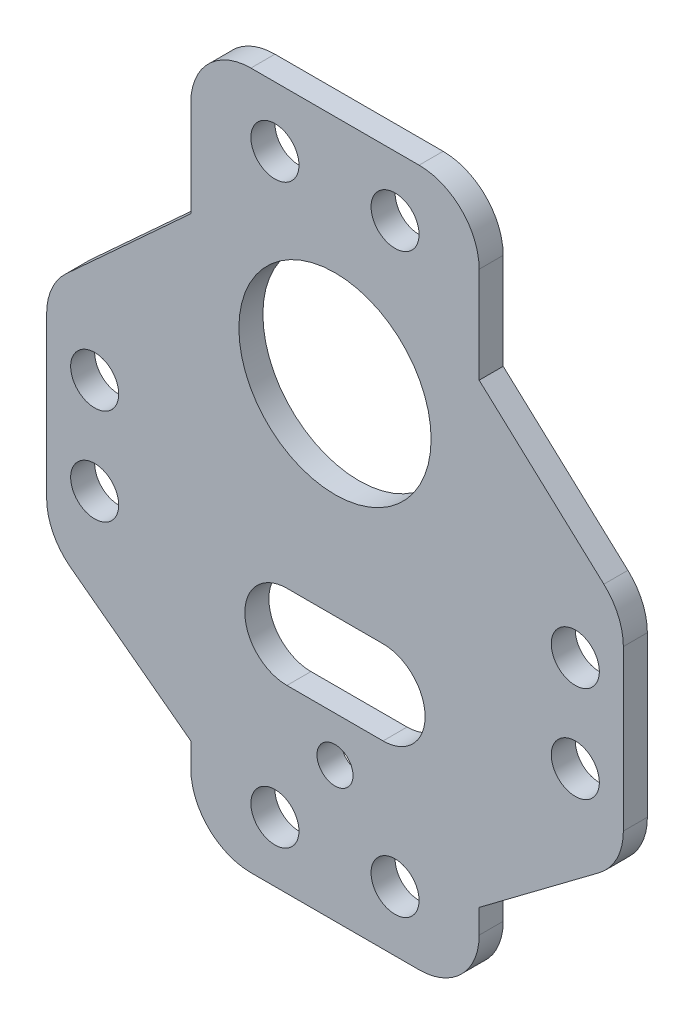
SolidWorks part; units mm, degrees
material "普通碳钢"
ref_plane "前视" through (0, 0, 0) normal (0, 0, 1) x (1, 0, 0)
ref_plane "上视" through (0, 0, 0) normal (0, 1, 0) x (1, 0, 0)
ref_plane "右视" through (0, 0, 0) normal (1, 0, 0) x (0, 0, -1)
sketch "草图1" plane through (0, 0, 0) normal (0, 0, 1) x (1, 0, 0)
  line L0 (0, 0) -> (0, -31) construction
  line L1 (0, -31) -> (-16, -43) construction
  line L2 (-16, -43) -> (-16, -61) construction
  line L3 (-16, -61) -> (4, -71) construction
  line L4 (4, -71) -> (12, -71) construction
  line L5 (0, 0) -> (16, 0) construction
  line L6 (8, 0) -> (8, -71) construction
  line L7 (32, -61) -> (12, -71) construction
  line L8 (32, -43) -> (32, -61) construction
  line L9 (16, -31) -> (32, -43) construction
  line L10 (16, 0) -> (16, -31) construction
  line L11 (4, -6) -> (12, -6) construction
  line L12 (12, -6) -> (12, -31) construction
  line L13 (4, -6) -> (4, -31.3218) construction
  line L14 (4, -58.5) -> (12, -58.5) construction
  line L15 (4, -55) -> (12, -55)
  line L16 (4, -62) -> (12, -62)
  line L17 (-4, -72) -> (20, -72) construction
  line L18 (-12, -48) -> (-12, -56) construction
  line L19 (-16, -52) -> (32, -52) construction
  line L20 (13, -24) -> (3, -24) construction
  line L21 (20, -19) -> (-4, -19)
  line L22 (20, -19) -> (20, -77) construction
  line L23 (20, -77) -> (-4, -77)
  line L24 (-4, -19) -> (-4, -77) construction
  line L25 (3, -24) -> (3, -72) construction
  line L26 (8, -24) -> (8, -72) construction
  line L27 (8, -48) -> (3, -48) construction
  line L28 (32, -43) -> (32, -61)
  line L29 (32, -61) -> (20, -70)
  line L30 (20, -70) -> (20, -77)
  line L31 (13, -70) -> (20, -70) construction
  line L32 (32, -43) -> (20, -32)
  line L33 (20, -32) -> (20, -19)
  line L34 (-4, -70) -> (-4, -77)
  line L35 (-16, -61) -> (-4, -70)
  line L36 (-16, -43) -> (-16, -61)
  line L37 (-16, -43) -> (-4, -32)
  line L38 (-4, -32) -> (-4, -19)
  circle A0 centre (8, -65.75) radius 1.5
  arc A1 (4, -55) -> (4, -62) centre (4, -58.5) ccw
  arc A2 (12, -62) -> (12, -55) centre (12, -58.5) ccw
  circle A3 centre (8, -38.25) radius 8
  circle A4 centre (3, -72) radius 2
  circle A5 centre (13, -72) radius 2
  circle A7 centre (-12, -48) radius 2
  circle A8 centre (-12, -56) radius 2
  circle A9 centre (28, -56) radius 2
  circle A10 centre (28, -48) radius 2
  circle A11 centre (3, -24) radius 2
  circle A12 centre (13, -24) radius 2
  point P20 (8, -58.5)
  dimension "D11" = 16
  dimension "D12" = 3.5
  dimension "D14" = 15
  dimension "D15" = 25
  dimension "D16" = 4
  dimension "D19" = 4
  dimension "D21" = 8
  dimension "D23" = 48
  dimension "D27" = 3
  dimension "D28" = 27.5
  dimension "D1" = 16
  dimension "D2" = 71
  dimension "D3" = 31
  dimension "D4" = 48
  dimension "D5" = 13.75
  dimension "D6" = 12
  dimension "D7" = 8
  dimension "D8" = 6
  dimension "D9" = 8
  dimension "D10" = 25
  dimension "D13" = 9
  dimension "D17" = 58
  dimension "D18" = 10
  dimension "D20" = 4
  dimension "D22" = 10
  dimension "D24" = 24
  dimension "D25" = 13
  dimension "D26" = 18
extrude "凸台-拉伸1" add sketch "草图1" along normal blind 2 contours A3
fillet "圆角1" radius 5 8 edges at (32, -61, 1) (32, -43, 1) (-16, -61, 1) (-16, -43, 1) (-4, -19, 1) (20, -19, 1) (20, -77, 1) (-4, -77, 1)
sketch "草图2" plane through (0, 0, 2) normal (0, 0, 1) x (1, 0, 0)
  line L0 (16, -38.25) -> (0, -38.25)
  line L1 (9.5, -65.75) -> (6.5, -65.75)
  circle A0 centre (8, -38.25) radius 8 construction
  circle A1 centre (8, -65.75) radius 1.5 construction
  circle A2 centre (8, -65.75) radius 1.5 construction
